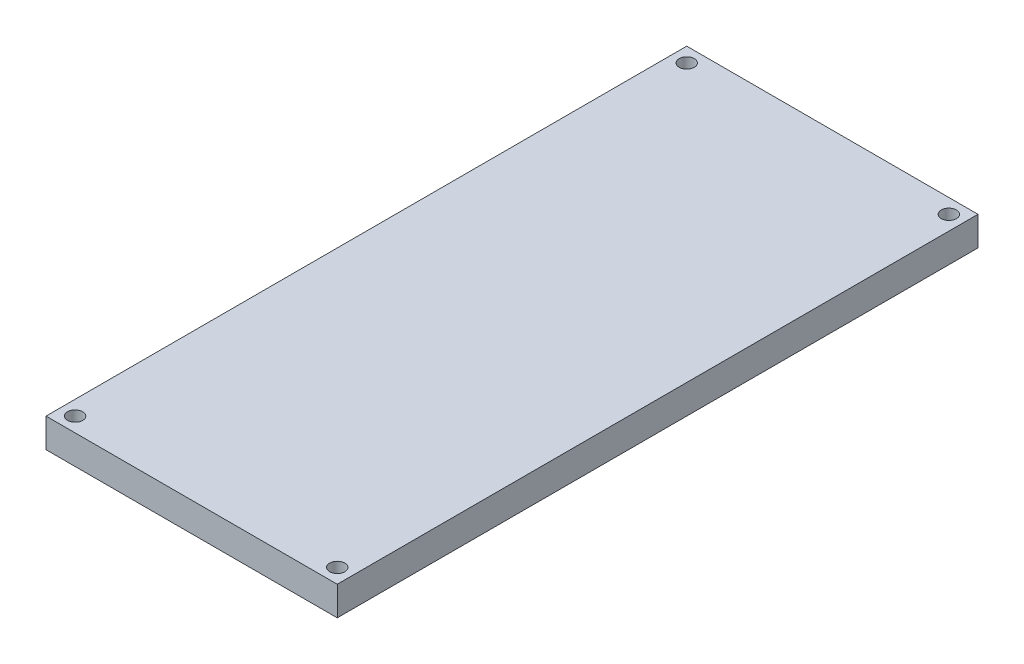
SolidWorks part; units mm, degrees
ref_plane "Front Plane" through (0, 0, 0) normal (0, 0, 1) x (1, 0, 0)
ref_plane "Top Plane" through (0, 0, 0) normal (0, 1, 0) x (1, 0, 0)
ref_plane "Right Plane" through (0, 0, 0) normal (1, 0, 0) x (0, 0, -1)
sketch "Sketch1" plane through (0, 0, 0) normal (0, 1, 0) x (1, 0, 0)
  line L1 (-31.75, -69.85) -> (31.75, -69.85)
  line L2 (-31.75, -69.85) -> (-31.75, 69.85)
  line L3 (-31.75, 69.85) -> (31.75, 69.85)
  line L4 (31.75, -69.85) -> (31.75, 69.85)
  line L5 (-31.75, -69.85) -> (31.75, 69.85) construction
  line L6 (-31.75, 69.85) -> (31.75, -69.85) construction
  point P0 (0, 0)
  dimension "D1" = 63.5
  dimension "D2" = 139.7
extrude "Boss-Extrude1" add sketch "Sketch1" along normal blind 6.35
sketch "Sketch3" plane through (0, 6.35, 0) normal (0, 1, 0) x (1, 0, 0)
  circle A8 centre (28.575, 66.675) radius 1.65 construction
  circle A9 centre (28.575, -66.675) radius 1.65 construction
  circle A10 centre (-28.575, -66.675) radius 1.65 construction
  circle A11 centre (-28.575, 66.675) radius 1.65 construction
  circle A12 centre (28.575, 66.675) radius 1.65
  circle A13 centre (28.575, -66.675) radius 1.65
  circle A14 centre (-28.575, -66.675) radius 1.65
  circle A15 centre (-28.575, 66.675) radius 1.65
extrude "Cut-Extrude1" cut sketch "Sketch3" against normal through all
